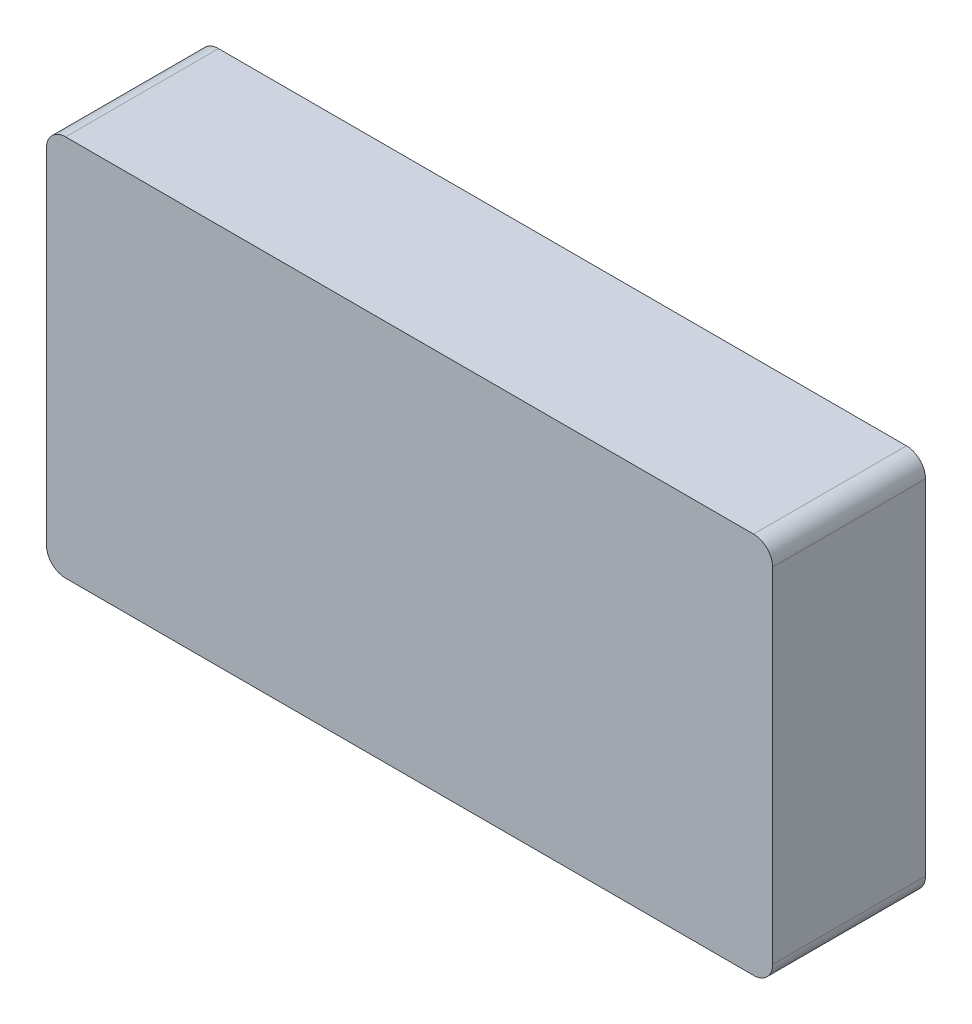
SolidWorks part; units mm, degrees
ref_plane "Ön Düzlem" through (0, 0, 0) normal (0, 0, 1) x (1, 0, 0)
ref_plane "Üst Düzlem" through (0, 0, 0) normal (0, 1, 0) x (1, 0, 0)
ref_plane "Sağ Düzlem" through (0, 0, 0) normal (1, 0, 0) x (0, 0, -1)
sketch "Çizim1" plane through (0, 0, 0) normal (0, 0, 1) x (1, 0, 0)
  line L1 (-90, 50) -> (90, 50)
  line L2 (-95, 45) -> (-95, -45)
  line L3 (-90, -50) -> (90, -50)
  line L4 (95, 45) -> (95, -45)
  line L5 (-95, 50) -> (95, -50) construction
  line L6 (-95, -50) -> (95, 50) construction
  arc A0 (90, 50) -> (95, 45) centre (90, 45) cw
  arc A1 (90, -50) -> (95, -45) centre (90, -45) ccw
  arc A2 (-95, -45) -> (-90, -50) centre (-90, -45) ccw
  arc A3 (-90, 50) -> (-95, 45) centre (-90, 45) ccw
  point P0 (0, 0)
  dimension "D3" = 5
  dimension "D1" = 100
  dimension "D2" = 190
extrude "Yükseklik-Ekstrüzyon1" add sketch "Çizim1" along normal blind 40
shell "İç Boşaltma1" thickness 3
sketch "Çizim2" plane through (0, 0, 40) normal (0, 0, 1) x (1, 0, 0)
  line L4 (90, 47) -> (-90, 47)
  line L5 (-92, 45) -> (-92, -45)
  line L6 (-90, -47) -> (90, -47)
  line L7 (92, -45) -> (92, 45)
  line L8 (90, 47) -> (-90, 47)
  line L9 (-92, 45) -> (-92, -45)
  line L10 (-90, -47) -> (90, -47)
  line L11 (92, -45) -> (92, 45)
  arc A4 (92, 45) -> (90, 47) centre (90, 45) ccw
  arc A5 (-90, 47) -> (-92, 45) centre (-90, 45) ccw
  arc A6 (-92, -45) -> (-90, -47) centre (-90, -45) ccw
  arc A7 (90, -47) -> (92, -45) centre (90, -45) ccw
  arc A8 (92, 45) -> (90, 47) centre (90, 45) ccw
  arc A9 (-90, 47) -> (-92, 45) centre (-90, 45) ccw
  arc A10 (-92, -45) -> (-90, -47) centre (-90, -45) ccw
  arc A11 (90, -47) -> (92, -45) centre (90, -45) ccw
  dimension "D1" = 0
extrude "Yükseklik-Ekstrüzyon2" add sketch "Çizim2" against normal blind 3
